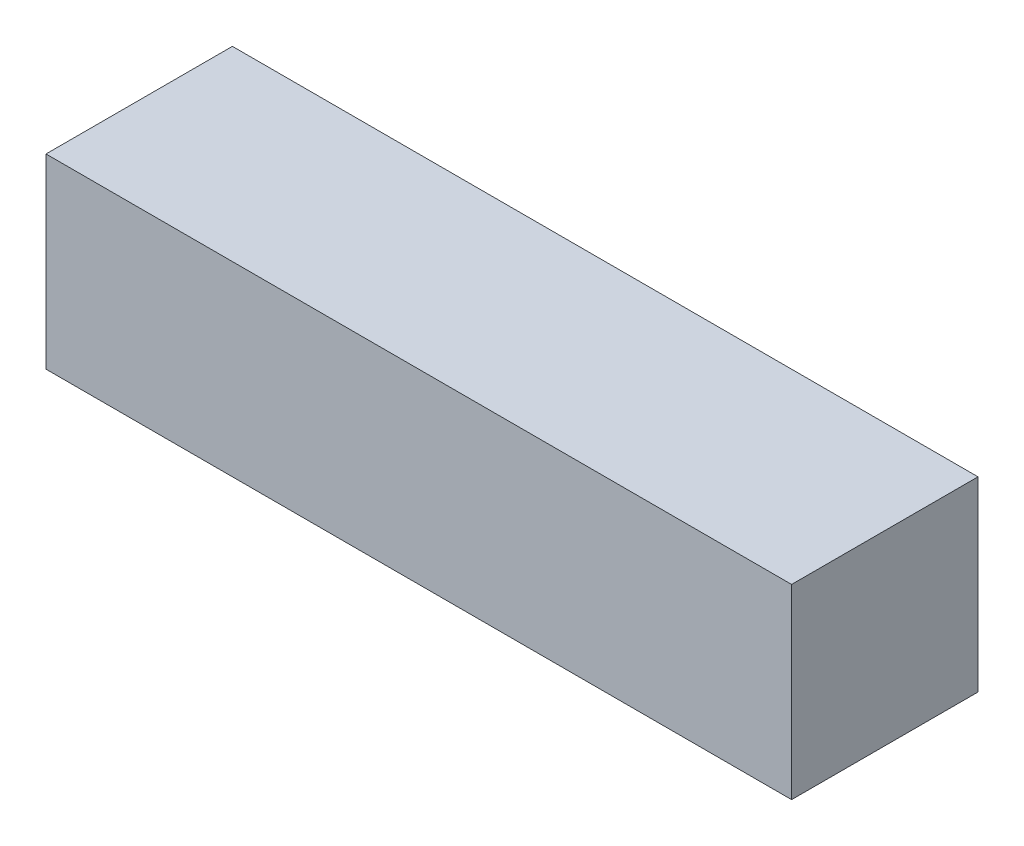
SolidWorks part; units mm, degrees
ref_plane "Alzado" through (0, 0, 0) normal (0, 0, 1) x (1, 0, 0)
ref_plane "Planta" through (0, 0, 0) normal (0, 1, 0) x (1, 0, 0)
ref_plane "Vista lateral" through (0, 0, 0) normal (1, 0, 0) x (0, 0, -1)
sketch "Croquis1" plane through (0, 0, 0) normal (0, 1, 0) x (1, 0, 0)
  line L1 (80, -20) -> (-80, -20)
  line L2 (80, -20) -> (80, 20)
  line L3 (80, 20) -> (-80, 20)
  line L4 (-80, -20) -> (-80, 20)
  line L5 (80, -20) -> (-80, 20) construction
  line L6 (80, 20) -> (-80, -20) construction
  point P0 (0, 0)
  dimension "D1" = 160
  dimension "D2" = 40
extrude "Saliente-Extruir1" add sketch "Croquis1" along normal blind 40
